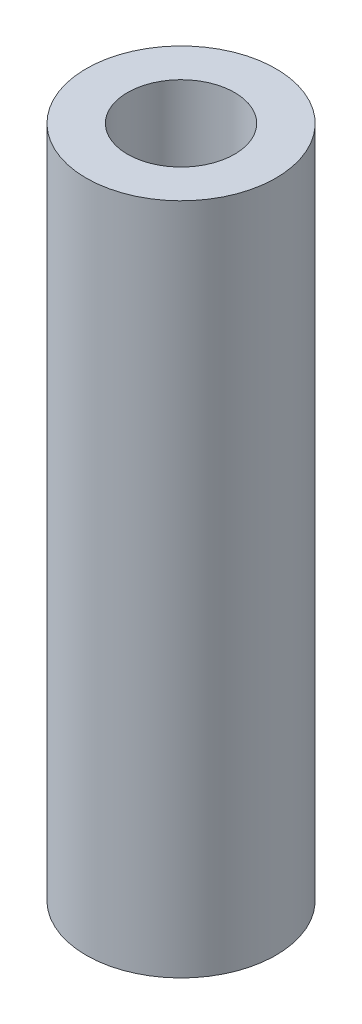
SolidWorks part; units mm, degrees
material "PP Kopolimer"
ref_plane "Płaszczyzna przednia" through (0, 0, 0) normal (0, 0, 1) x (1, 0, 0)
ref_plane "Płaszczyzna górna" through (0, 0, 0) normal (0, 1, 0) x (1, 0, 0)
ref_plane "Płaszczyzna prawa" through (0, 0, 0) normal (1, 0, 0) x (0, 0, -1)
sketch "Szkic1" plane through (0, 0, 0) normal (0, 1, 0) x (1, 0, 0)
  circle A0 centre (0, 0) radius 35
  circle A1 centre (0, 0) radius 62
  dimension "D1" = 70
  dimension "D2" = 124
extrude "Dodanie-wyciągnięcie1" add sketch "Szkic1" along normal blind 440
ref_plane "Płaszczyzna1" through (0, 440, 0) normal (0, 1, 0) x (1, 0, 0)
